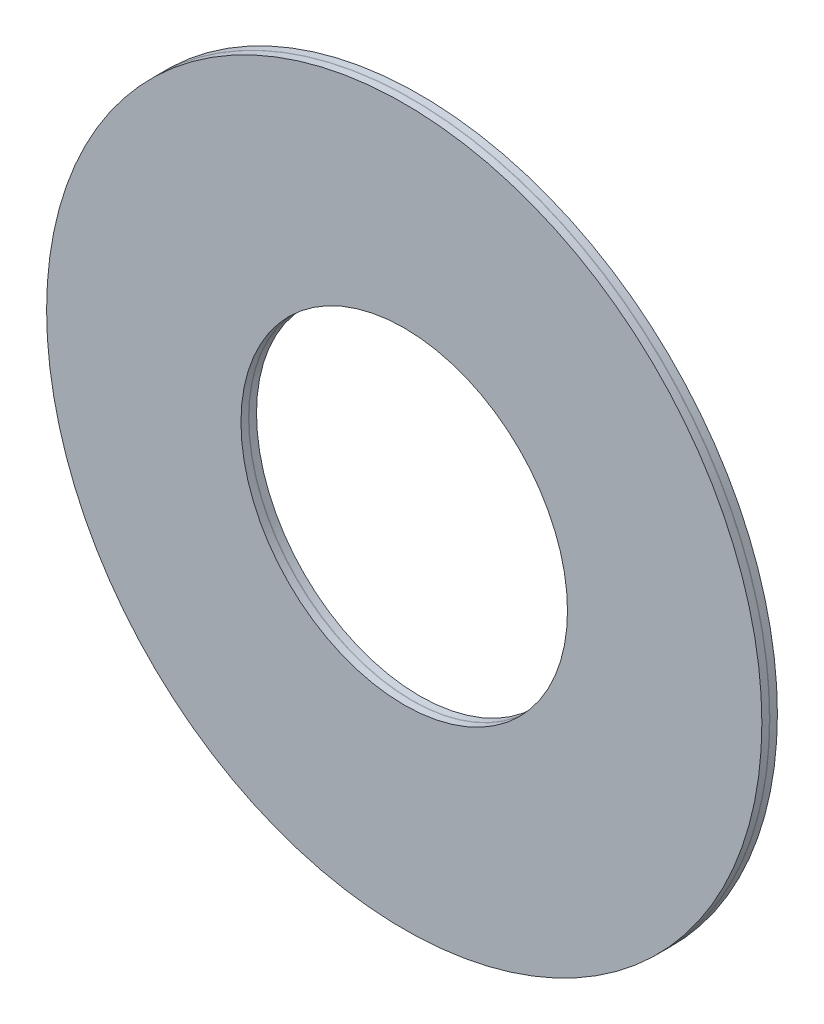
SolidWorks part; units mm, degrees
ref_plane "Front Plane" through (0, 0, 0) normal (0, 0, 1) x (1, 0, 0)
ref_plane "Top Plane" through (0, 0, 0) normal (0, 1, 0) x (1, 0, 0)
ref_plane "Right Plane" through (0, 0, 0) normal (1, 0, 0) x (0, 0, -1)
sketch "Sketch1" plane through (0, 0, 0) normal (0, 0, 1) x (1, 0, 0)
  line L0 (0, 36.5125) -> (0, -36.5125) construction
  line L1 (-36.5125, 0) -> (36.5125, 0) construction
  circle A0 centre (0, 0) radius 36.5125 construction
  circle A1 centre (0, 0) radius 16.6687 construction
  point P8 (0, -16.6687)
  point P9 (16.6687, 0)
  point P10 (0, 16.6687)
  point P11 (-16.6687, 0)
  point P13 (0, 0)
  dimension "D1" = 19.8437
  dimension "OD" = 73.025
  dimension "ID" = 33.3375
sketch "Sketch2" plane through (0, 0, 0) normal (1, 0, 0) x (0, 0, -1)
  line L0 (0, -36.5125) -> (0, 36.5125) construction
  line L1 (0.7938, 36.5125) -> (-0.7938, 36.5125) construction
  line L2 (0.7938, 36.5125) -> (0.7938, -36.5125) construction
  line L3 (0.7938, -36.5125) -> (-0.7938, -36.5125) construction
  line L4 (-0.7938, 36.5125) -> (-0.7938, -36.5125) construction
  line L5 (0.7938, 0) -> (-0.7938, 0) construction
  line L8 (-0.7938, 16.6687) -> (0.7938, 16.6687) construction
  line L9 (-0.7938, -16.6687) -> (0.7938, -16.6687) construction
  point P8 (0, 0)
  dimension "Thickness" = 1.5875
sketch "Sketch3" plane through (0, 0, 0) normal (1, 0, 0) x (0, 0, -1)
  line L0 (-0.0254, 36.5125) -> (0.0254, 36.5125)
  line L10 (0.7938, 36.5125) -> (-0.7938, 36.5125) construction
  line L11 (-0.0254, 36.5125) -> (-0.0254, 16.6688)
  line L12 (-0.7938, 16.6687) -> (0.7938, 16.6687) construction
  line L13 (-0.0254, 16.6688) -> (0.0254, 16.6688)
  line L16 (0.0254, 16.6688) -> (0.0254, 36.5125)
  point P5 (0, 36.5125)
  dimension "D1" = 0.0508
revolve "Revolve1" add sketch "Sketch3" angle 360 about L5
sketch "Sketch4" plane through (0, 0, 0) normal (1, 0, 0) x (0, 0, -1)
  line L0 (-0.0254, 36.5125) -> (-0.7938, 36.5125)
  line L1 (-0.7938, 36.5125) -> (-0.7938, 16.6687)
  line L2 (-0.7938, 16.6687) -> (-0.0254, 16.6688)
  line L3 (-0.0254, 16.6688) -> (-0.0254, 36.5125)
  line L4 (0.0254, 36.5125) -> (0.7938, 36.5125)
  line L5 (0.7938, 36.5125) -> (0.7938, 16.6687)
  line L6 (0.7938, 16.6687) -> (0.0254, 16.6688)
  line L7 (0.0254, 16.6688) -> (0.0254, 36.5125)
revolve "Revolve2" add sketch "Sketch4" angle 360 about L5
